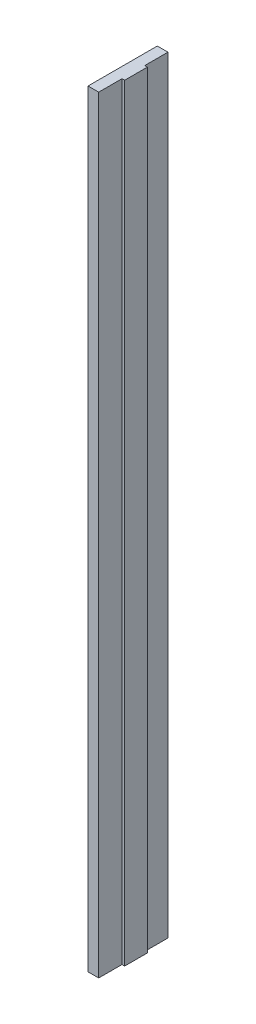
SolidWorks part; units mm, degrees
ref_plane "Plan de face" through (0, 0, 0) normal (0, 0, 1) x (1, 0, 0)
ref_plane "Plan de dessus" through (0, 0, 0) normal (0, 1, 0) x (1, 0, 0)
ref_plane "Plan de droite" through (0, 0, 0) normal (1, 0, 0) x (0, 0, -1)
sketch "Esquisse1" plane through (0, 0, 0) normal (1, 0, 0) x (0, 0, -1)
  line L1 (-41.275, 457.2) -> (41.275, 457.2)
  line L2 (-41.275, 457.2) -> (-41.275, -457.2)
  line L3 (-41.275, -457.2) -> (41.275, -457.2)
  line L4 (41.275, 457.2) -> (41.275, -457.2)
  line L5 (-41.275, 457.2) -> (41.275, -457.2) construction
  line L6 (-41.275, -457.2) -> (41.275, 457.2) construction
  point P0 (0, 0)
  dimension "D1" = 82.55
  dimension "D2" = 914.4
extrude "Boss.-Extru.1" add sketch "Esquisse1" along normal blind 15.875
sketch "Esquisse3" plane through (0, 457.2, 0) normal (0, 1, 0) x (1, 0, 0)
  line L0 (15.875, 41.275) -> (0, 41.275) construction
  line L1 (12.7, 41.275) -> (38.1, 41.275)
  line L2 (12.7, 41.275) -> (12.7, 13.5)
  line L3 (12.7, 13.5) -> (19.05, 13.5)
  line L7 (19.05, 13.5) -> (19.05, -13.5)
  line L8 (38.1, 41.275) -> (38.1, -41.275)
  line L9 (0, 0) -> (38.1, 0) construction
  line L13 (12.7, -13.5) -> (19.05, -13.5)
  line L14 (12.7, -41.275) -> (12.7, -13.5)
  line L15 (12.7, -41.275) -> (38.1, -41.275)
  line L16 (15.875, 41.275) -> (15.875, -41.275) construction
  point P4 (19.05, 40.6731)
  point P8 (19.05, -40.6731)
  point P17 (19.05, 0)
  dimension "D1" = 3.175
  dimension "D2" = 27
  dimension "D3" = 25.4
  dimension "D4" = 6.35
extrude "Enlèv. mat.-Extru.1" cut sketch "Esquisse3" against normal through all
